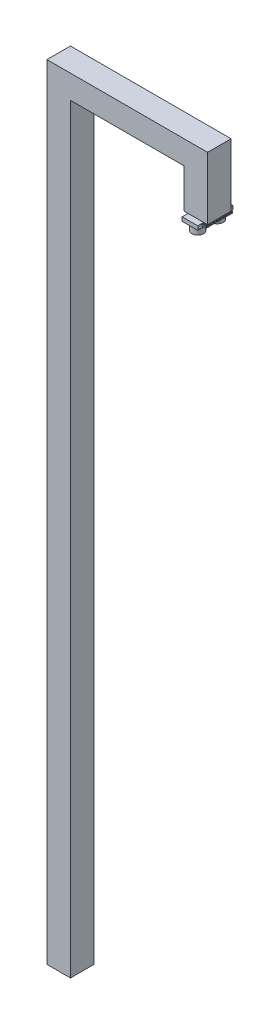
SolidWorks part; units mm, degrees
ref_plane "Front Plane" through (0, 0, 0) normal (0, 0, 1) x (1, 0, 0)
ref_plane "Top Plane" through (0, 0, 0) normal (0, 1, 0) x (1, 0, 0)
ref_plane "Right Plane" through (0, 0, 0) normal (1, 0, 0) x (0, 0, -1)
sketch "Sketch1" plane through (0, 0, 0) normal (0, 1, 0) x (1, 0, 0)
  line L1 (-1.5, 1.5) -> (1.5, 1.5)
  line L2 (-1.5, 1.5) -> (-1.5, -1.5)
  line L3 (-1.5, -1.5) -> (1.5, -1.5)
  line L4 (1.5, 1.5) -> (1.5, -1.5)
  line L5 (-1.5, 1.5) -> (1.5, -1.5) construction
  line L6 (-1.5, -1.5) -> (1.5, 1.5) construction
  point P0 (0, 0)
  dimension "D1" = 3
  dimension "D2" = 3
extrude "Boss-Extrude1" add sketch "Sketch1" along normal blind 100
sketch "Sketch3" plane through (1.5, 0, 0) normal (1, 0, 0) x (0, 0, -1)
  line L0 (1.5, 100) -> (1.5, 0) construction
  line L1 (-1.5, 100) -> (1.5, 100)
  line L2 (-1.5, 100) -> (-1.5, 97)
  line L3 (-1.5, 97) -> (1.5, 97)
  line L4 (1.5, 100) -> (1.5, 97)
  dimension "D1" = 3
extrude "Boss-Extrude2" add sketch "Sketch3" along normal blind 17.5
sketch "Sketch4" plane through (0, 97, 0) normal (0, -1, 0) x (1, 0, 0)
  line L0 (19, -1.5) -> (1.5, -1.5) construction
  line L1 (19, 1.5) -> (16, 1.5)
  line L2 (19, 1.5) -> (19, -1.5)
  line L3 (19, -1.5) -> (16, -1.5)
  line L4 (16, 1.5) -> (16, -1.5)
  dimension "D1" = 3
  dimension "D2" = 3
extrude "Boss-Extrude3" add sketch "Sketch4" along normal blind 5
sketch "Sketch5" plane through (0, 92, 0) normal (0, -1, 0) x (1, 0, 0)
  line L0 (19, 1.5) -> (16, 1.5) construction
  line L1 (16.5, 2.25) -> (18.5, 2.25)
  line L2 (16.5, 2.25) -> (16.5, -2.25)
  line L3 (16.5, -2.25) -> (18.5, -2.25)
  line L4 (18.5, 2.25) -> (18.5, -2.25)
  line L5 (16.5, 2.25) -> (18.5, -2.25) construction
  line L6 (16.5, -2.25) -> (18.5, 2.25) construction
  line L7 (19, -1.5) -> (19, 1.5) construction
  point P0 (17.5, 0)
  dimension "D1" = 2
  dimension "D2" = 4.5
  dimension "D3" = 1.5
  dimension "D4" = 1.5
extrude "Boss-Extrude4" add sketch "Sketch5" along normal blind 0.5
sketch "Sketch6" plane through (0, 91.5, 0) normal (0, -1, 0) x (1, 0, 0)
  line L0 (18.5, -2.25) -> (18.5, 2.25) construction
  line L1 (18.5, -1.5) -> (18.5, 1.5) construction
  line L2 (18.5, 2.25) -> (16.5, 2.25) construction
  line L3 (16.5, -2.25) -> (18.5, -2.25) construction
  circle A0 centre (17.5, 1.25) radius 0.75
  circle A1 centre (17.5, -1.25) radius 0.75
  dimension "D1" = 1
  dimension "D2" = 1
  dimension "D3" = 1
  dimension "D4" = 1
  dimension "D5" = 1.5
  dimension "D6" = 1.5
extrude "Boss-Extrude5" add sketch "Sketch6" along normal blind 1
sketch "Sketch7" plane through (18.5, 0, 0) normal (1, 0, 0) x (0, 0, -1)
  text T0 "<b>ULTRASONIC SENSOR</b>\r\n" font "Century Gothic" height 0.25
extrude "Boss-Extrude6" add sketch "Sketch7" along normal blind 0.5
